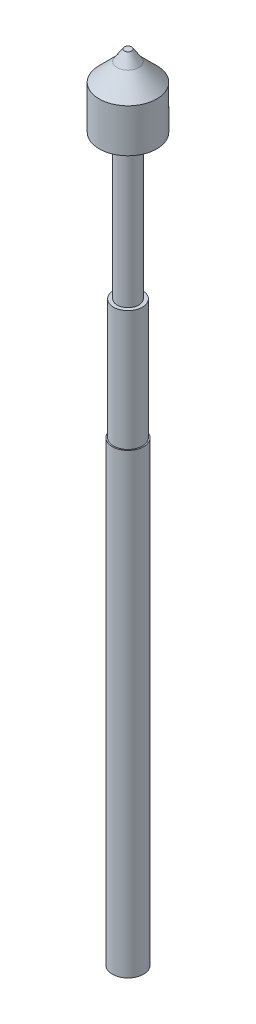
SolidWorks part; units mm, degrees
ref_plane "前视基准面" through (0, 0, 0) normal (0, 0, 1) x (1, 0, 0)
ref_plane "上视基准面" through (0, 0, 0) normal (0, 1, 0) x (1, 0, 0)
ref_plane "右视基准面" through (0, 0, 0) normal (1, 0, 0) x (0, 0, -1)
other "Configuration Table"
sketch "草图1" plane through (0, 0, 0) normal (0, 1, 0) x (1, 0, 0)
  circle A0 centre (0, 0) radius 0.65
  dimension "D1" = 1.3
extrude "凸台-拉伸1" add sketch "草图1" along normal blind 19
sketch "草图2" plane through (0, 19, 0) normal (0, 1, 0) x (1, 0, 0)
  circle A0 centre (0, 0) radius 0.6
  dimension "D1" = 1.2
extrude "凸台-拉伸2" add sketch "草图2" along normal blind 5
sketch "草图3" plane through (0, 24, 0) normal (0, 1, 0) x (1, 0, 0)
  circle A0 centre (0, 0) radius 0.45
  dimension "D1" = 0.9
extrude "凸台-拉伸3" add sketch "草图3" along normal blind 9
sketch "草图5" plane through (0, 0, 0) normal (0, 0, 1) x (1, 0, 0)
  line L0 (0.65, 19) -> (0.6, 19.8)
  line L1 (0.6, 19) -> (0.6, 24) construction
  line L2 (0.6, 19.8) -> (0.6, 19)
  line L3 (0.6, 19) -> (0.65, 19)
  line L4 (0, 0) -> (0, 0.7809) construction
  line L7 (0, 0.3) -> (0.95, 0.3) construction
  line L8 (0.65, 0) -> (0.65, 19) construction
  line L9 (0.65, 0.6) -> (0.65, 0)
  line L10 (-0.65, 0) -> (0.65, 0) construction
  line L11 (0, 2.2) -> (0.915, 2.2) construction
  line L12 (0.65, 2.5) -> (0.65, 1.9)
  arc A0 (0.65, 0.6) -> (0.65, 0) centre (0.65, 0.3) cw
  arc A1 (0.65, 2.5) -> (0.65, 1.9) centre (0.6127, 2.2) cw
  dimension "D1" = 0.8
  dimension "D2" = 0.95
  dimension "D3" = 0.915
  dimension "D4" = 2.5
sketch "草图6" plane through (0, 0, 0) normal (0, 0, 1) x (1, 0, 0)
  line L0 (0, 0) -> (0, -1.2565) construction
  line L2 (0, 33) -> (-1.2, 31.8)
  line L3 (0.45, 33) -> (-0.45, 33) construction
  line L4 (-1.2, 31.8) -> (-1.2, 30)
  line L5 (-1.2, 30) -> (0, 30)
  line L6 (0, 30) -> (0, 33)
  dimension "D1" = 1.2
  dimension "D2" = 3
  dimension "D3" = 135
revolve "旋转2" add sketch "草图6" angle 360 about L0
sketch "草图7" plane through (0, 0, 0) normal (0, 0, 1) x (1, 0, 0)
  line L0 (0, 0) -> (0, -1.5384) construction
  line L7 (0.45, 33) -> (0.15, 33)
  line L8 (0.45, 33) -> (-0.45, 33) construction
  line L9 (0.15, 33) -> (0.45, 32.55)
  line L10 (0.45, 32.55) -> (-0.45, 32.55) construction
  line L11 (0.45, 32.55) -> (0.45, 33) construction
  line L12 (0.45, 32.55) -> (0.45, 33)
  dimension "D1" = 0.3
revolve "切除-旋转5" cut sketch "草图7" angle 360 about L0
